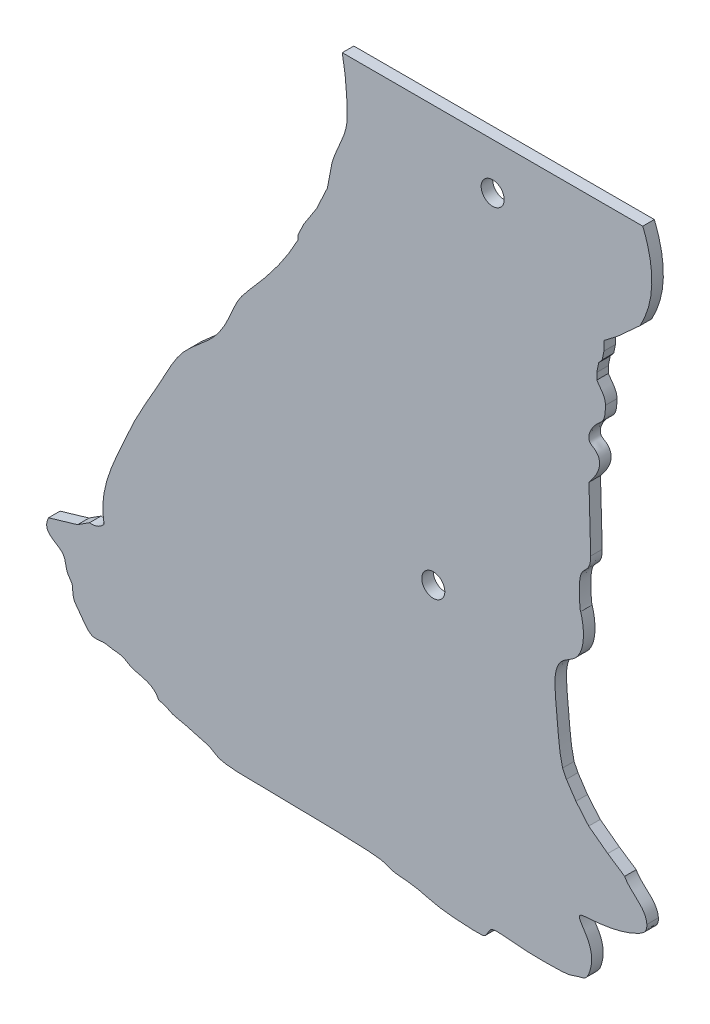
SolidWorks part; units mm, degrees
ref_plane "Front Plane" through (0, 0, 0) normal (0, 0, 1) x (1, 0, 0)
ref_plane "Top Plane" through (0, 0, 0) normal (0, 1, 0) x (1, 0, 0)
ref_plane "Right Plane" through (0, 0, 0) normal (1, 0, 0) x (0, 0, -1)
sketch "Sketch1" plane through (0, 0, 0) normal (0, 0, 1) x (1, 0, 0)
  line L0 (134.6667, 500.5) -> (673.3333, 500.5) construction
  line L2 (167.2022, 42.2012) -> (162.5517, 45.3095)
  line L3 (162.5517, 45.3095) -> (157.3147, 49.2233)
  line L4 (157.3147, 49.2233) -> (153.7929, 53.3936)
  line L5 (153.7929, 53.3936) -> (151.1787, 57.3127)
  line L6 (151.1787, 57.3127) -> (150.1126, 59.4633)
  line L7 (157.3755, 131.2295) -> (157.854, 113.8805)
  line L8 (159.5344, 156.6595) -> (159.5344, 158.498)
  line L9 (159.5344, 158.498) -> (160.0825, 161.1123)
  line L10 (160.0825, 161.1123) -> (161.0243, 162.2425)
  line L11 (161.0243, 162.2425) -> (161.5128, 164.5724)
  line L12 (161.5128, 164.5724) -> (161.5128, 167.1023)
  line L13 (161.5128, 167.1023) -> (165.1835, 169.9013)
  line L14 (165.1835, 169.9013) -> (171.472, 175.6217)
  line L15 (86.5908, 171.7678) -> (85.3882, 165.3811)
  line L16 (89.473, 199.6877) -> (172.1964, 199.6877)
  line L17 (85.3882, 165.3811) -> (82.4023, 158.9826)
  line L18 (82.4023, 158.9826) -> (78.8266, 153.4325)
  line L19 (78.8266, 153.4325) -> (77.3096, 150.1819)
  line L20 (77.3096, 150.1819) -> (77.3096, 148.973)
  line L21 (89.473, 199.6877) -> (189.494, 199.6877) construction
  line L22 (127.4919, 8.5553) -> (214.3131, 8.5553) construction
  line L23 (8.6124, 48.3831) -> (8.6124, -14.4171) construction
  line L24 (173.32, 33.793) -> (173.32, -11.6797) construction
  circle A0 centre (130.8722, 186.9242) radius 3.1743
  circle A1 centre (114.5276, 85.3159) radius 3.1743
  spline S0 degree 1 poles (8.6124, 48.3831) (16.6111, 50.7357) knots 0 0 1 1
  spline S1 degree 1 poles (19.9047, 52.853) (16.6111, 50.7357) knots 0 0 1 1
  spline S2 degree 3 poles (23.9041, 54.4997) (22.542, 62.0444) (27.1512, 71.7199) (33.1716, 85.6736) (39.4703, 95.7444) (45.0444, 107.3971) (54.1548, 113.0729) (58.3579, 120.6747) (60.6418, 126.7915) (68.4166, 135.2748) (73.9208, 142.4894) (77.3096, 148.973) knots 0 0 0 0 0.194457 0.285904 0.412664 0.517827 0.629269 0.691339 0.750377 0.804905 1 1 1 1
  spline S3 degree 2 poles (19.9047, 52.853) (22.4371, 52.6083) (23.9041, 54.4997) knots 0 0 0 1 1 1
  spline S4 degree 3 poles (8.6124, 48.3831) (6.5691, 43.9628) (13.6478, 43.7296) (13.2535, 37.9915) (15.2259, 36.1128) (15.2445, 34.2074) (15.4257, 32.4092) (16.9812, 30.3171) (18.455, 28.2086) (20.7273, 25.6089) (23.6404, 26.5196) (26.3788, 25.705) (29.0077, 25.795) (31.226, 24.0079) (34.9468, 23.3493) (38.0007, 22.2222) (38.8831, 20.145) knots 0 0 0 0 0.18572 0.273851 0.320038 0.350192 0.393849 0.435551 0.514834 0.569195 0.638874 0.687587 0.755837 0.801068 0.865551 1 1 1 1
  spline S5 degree 3 poles (38.8831, 20.145) (41.2875, 19.5656) (42.3458, 18.5073) (45.4199, 18.1546) (49.7538, 16.7939) (52.7775, 16.1892) (54.7934, 14.8285) (56.3556, 14.1734) (60.1352, 13.7702) (61.5463, 13.7702) (99.2418, 13.2159) (101.2856, 12.2232) (103.9594, 11.2977) (106.3246, 11.2977) (111.5693, 10.5778) (115.1686, 9.2409) (123.9098, 8.5211) (128.0233, 8.5211) (128.9488, 8.7267) (129.9772, 10.7835) (131.0055, 11.8119) (139.3353, 10.7835) (144.7857, 10.7835) (151.9843, 10.7835) (154.3496, 12.1204) (156.7148, 12.1204) (158.1545, 16.0282) (158.1545, 19.319) (157.3318, 21.6842) (156.4063, 23.3296) (153.7325, 27.1346) (157.3189, 27.1346) (163.0629, 27.7755) (167.4392, 28.9243) (170.3933, 30.1004) (172.4447, 31.2857) (173.2037, 32.3228) (173.32, 33.1913) (173.32, 33.793) knots 0 0 0 0 0.028571 0.057143 0.085714 0.114286 0.142857 0.171429 0.2 0.228571 0.257143 0.285714 0.314286 0.342857 0.371429 0.4 0.428571 0.457143 0.485714 0.514286 0.542857 0.571429 0.6 0.628571 0.657143 0.685714 0.714286 0.742857 0.771429 0.8 0.828571 0.857143 0.885714 0.914286 0.942857 0.971429 0.985714 1 1 1 1
  spline S6 degree 3 poles (173.32, 33.793) (173.0564, 37.6266) (168.8406, 39.1122) (167.2022, 42.2012) knots 0 0 0 0 1 1 1 1
  spline S7 degree 3 poles (150.1126, 59.4633) (148.9568, 63.837) (148.9486, 71.4394) (146.8505, 84.0514) (156.4694, 88.1502) (156.2475, 95.5102) (155.0853, 99.2556) knots 0 0 0 0 0.308783 0.618237 0.704406 1 1 1 1
  spline S8 degree 3 poles (157.854, 113.8805) (157.8564, 113.8699) (157.8506, 110.688) (155.3081, 109.3846) (154.4188, 105.0533) (154.8696, 99.4834) (155.0853, 99.2556) knots 0 0 0 0 0.124799 0.365608 0.555267 1 1 1 1
  spline S9 degree 3 poles (161.8927, 151.8072) (161.9125, 149.0313) (161.4499, 147.7916) (158.4451, 145.386) (156.1309, 141.3803) (158.8302, 140.0435) (161.6487, 137.4079) (159.4597, 133.7277) (157.3755, 131.2295) knots 0 0 0 0 0.190659 0.228613 0.488803 0.534056 0.585176 1 1 1 1
  spline S10 degree 3 poles (159.5344, 156.6595) (160.7867, 154.8399) (162.0055, 153.6124) (161.8927, 151.8072) knots 0 0 0 0 1 1 1 1
  spline S11 degree 2 poles (172.1964, 199.6877) (177.5125, 186.6119) (171.472, 175.6217) knots 0 0 0 1 1 1
  spline S12 degree 3 poles (89.473, 199.6877) (90.4497, 194.8375) (90.826, 189.8378) (90.8383, 180.2807) (87.6783, 176.1914) (86.5908, 171.7678) knots 0 0 0 0 0.517811 0.520823 1 1 1 1
  point P125 (0, 0)
  dimension "D2" = 164.7075
extrude "Boss-Extrude2" add sketch "Sketch1" along normal blind 3.175
